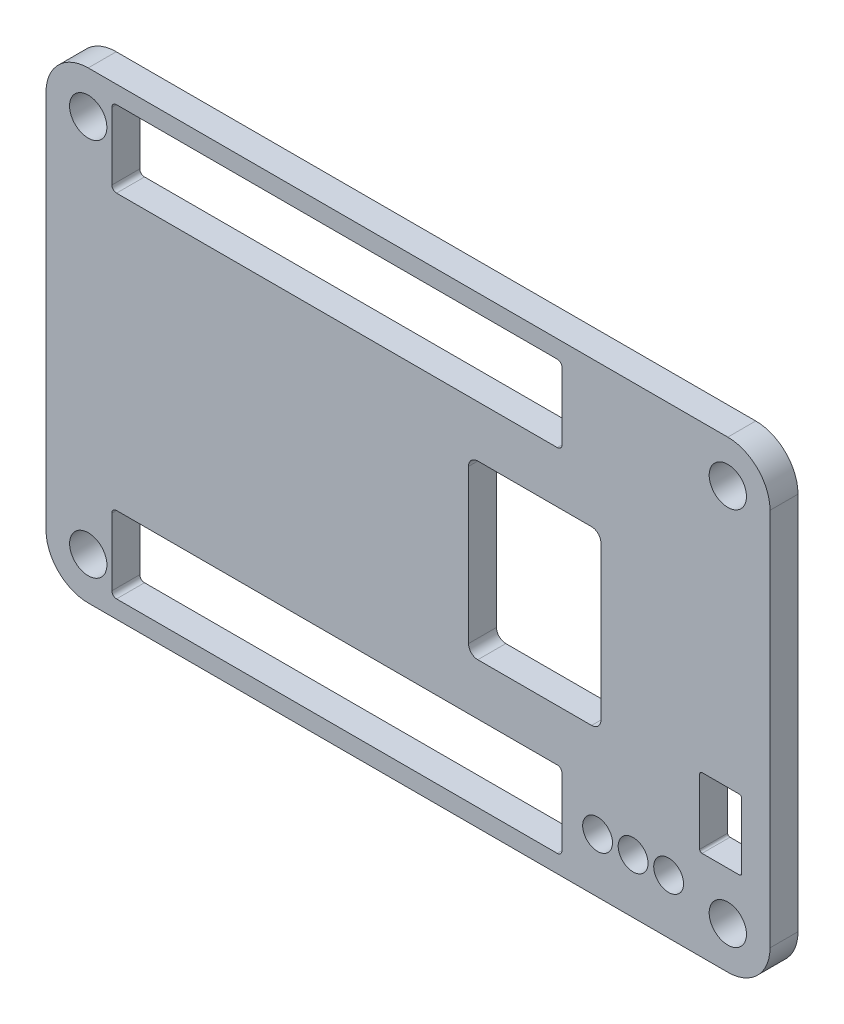
SolidWorks part; units mm, degrees
ref_plane "前视基准面" through (0, 0, 0) normal (0, 0, 1) x (1, 0, 0)
ref_plane "上视基准面" through (0, 0, 0) normal (0, 1, 0) x (1, 0, 0)
ref_plane "右视基准面" through (0, 0, 0) normal (1, 0, 0) x (0, 0, -1)
sketch "草图1" plane through (0, 0, 0) normal (0, 0, 1) x (1, 0, 0)
  line L0 (-34.285, 24.845) -> (34.285, 24.845)
  line L1 (-34.285, 22.845) -> (34.285, 22.845) construction
  line L2 (-36.815, 20.315) -> (-36.815, -20.315) construction
  line L3 (-34.285, -22.845) -> (34.285, -22.845) construction
  line L4 (36.815, 20.315) -> (36.815, -20.315) construction
  line L5 (-36.815, 22.845) -> (36.815, -22.845) construction
  line L6 (-36.815, -22.845) -> (36.815, 22.845) construction
  line L7 (-34.29, 20.32) -> (34.29, 20.32) construction
  line L8 (-34.29, 20.32) -> (-34.29, -20.32) construction
  line L9 (-34.29, -20.32) -> (34.29, -20.32) construction
  line L10 (34.29, 20.32) -> (34.29, -20.32) construction
  line L11 (-34.29, 20.32) -> (34.29, -20.32) construction
  line L12 (-34.29, -20.32) -> (34.29, 20.32) construction
  line L13 (38.815, 20.315) -> (38.815, -20.315)
  line L14 (-34.285, -24.845) -> (34.285, -24.845)
  line L15 (-38.815, 20.315) -> (-38.815, -20.315)
  arc A0 (-36.815, -20.315) -> (-34.285, -22.845) centre (-34.285, -20.315) ccw construction
  arc A1 (34.285, -22.845) -> (36.815, -20.315) centre (34.285, -20.315) ccw construction
  arc A2 (36.815, 20.315) -> (34.285, 22.845) centre (34.285, 20.315) ccw construction
  arc A3 (-36.815, 20.315) -> (-34.285, 22.845) centre (-34.285, 20.315) cw construction
  circle A4 centre (34.29, 20.32) radius 2
  circle A5 centre (34.29, -20.32) radius 2
  circle A6 centre (-34.29, 20.32) radius 2
  circle A7 centre (-34.285, -20.315) radius 2
  arc A8 (38.815, 20.315) -> (34.285, 24.845) centre (34.285, 20.315) ccw
  arc A9 (34.285, -24.845) -> (38.815, -20.315) centre (34.285, -20.315) ccw
  arc A10 (-38.815, -20.315) -> (-34.285, -24.845) centre (-34.285, -20.315) ccw
  arc A11 (-38.815, 20.315) -> (-34.285, 24.845) centre (-34.285, 20.315) cw
  point P0 (0, 0)
  point P18 (0, 0)
  dimension "D3" = 2.53
  dimension "D6" = 4
  dimension "D7" = 4
  dimension "D8" = 4
  dimension "D9" = 4
  dimension "D1" = 73.63
  dimension "D2" = 45.69
  dimension "D4" = 68.58
  dimension "D5" = 40.64
  dimension "D10" = 2
extrude "凸台-拉伸1" add sketch "草图1" along normal mid plane 3
sketch "草图2" plane through (0, 0, 1.5) normal (0, 0, 1) x (1, 0, 0)
  line L0 (-38.815, 20.315) -> (-38.815, -20.315) construction
  line L1 (-31.255, 22.945) -> (16.005, 22.945)
  line L2 (-31.755, 22.445) -> (-31.755, 15.235)
  line L3 (-31.255, 14.735) -> (16.005, 14.735)
  line L4 (16.505, 22.445) -> (16.505, 15.235)
  line L5 (-31.755, 22.945) -> (16.505, 14.735) construction
  line L6 (-31.755, 14.735) -> (16.505, 22.945) construction
  line L7 (38.815, -20.315) -> (38.815, 20.315) construction
  line L8 (34.285, 24.845) -> (-34.285, 24.845) construction
  line L9 (0, 0) -> (13.585, 0) construction
  line L10 (-31.755, -22.445) -> (-31.755, -15.235)
  line L11 (-31.255, -22.945) -> (16.005, -22.945)
  line L12 (16.505, -22.445) -> (16.505, -15.235)
  line L13 (-31.255, -14.735) -> (16.005, -14.735)
  line L14 (-34.285, -24.845) -> (34.285, -24.845) construction
  line L16 (31.525, -7.685) -> (35.525, -7.685)
  line L17 (31.275, -7.935) -> (31.275, -14.935)
  line L18 (31.525, -15.185) -> (35.525, -15.185)
  line L19 (35.775, -7.935) -> (35.775, -14.935)
  line L20 (31.275, -7.685) -> (35.775, -15.185) construction
  line L21 (31.275, -15.185) -> (35.775, -7.685) construction
  line L22 (7.485, 9.225) -> (19.685, 9.225)
  line L23 (6.485, 8.225) -> (6.485, -8.225)
  line L24 (7.485, -9.225) -> (19.685, -9.225)
  line L25 (20.685, 8.225) -> (20.685, -8.225)
  line L26 (6.485, 9.225) -> (20.685, -9.225) construction
  line L27 (6.485, -9.225) -> (20.685, 9.225) construction
  arc A0 (-31.255, 14.735) -> (-31.755, 15.235) centre (-31.255, 15.235) cw
  arc A1 (-31.755, 22.445) -> (-31.255, 22.945) centre (-31.255, 22.445) cw
  arc A2 (16.005, 22.945) -> (16.505, 22.445) centre (16.005, 22.445) cw
  arc A3 (16.505, 15.235) -> (16.005, 14.735) centre (16.005, 15.235) cw
  arc A4 (-31.255, -14.735) -> (-31.755, -15.235) centre (-31.255, -15.235) ccw
  arc A5 (-31.755, -22.445) -> (-31.255, -22.945) centre (-31.255, -22.445) ccw
  arc A6 (16.005, -22.945) -> (16.505, -22.445) centre (16.005, -22.445) ccw
  arc A7 (16.505, -15.235) -> (16.005, -14.735) centre (16.005, -15.235) ccw
  circle A8 centre (27.945, -19.005) radius 1.6
  circle A9 centre (24.135, -19.005) radius 1.6
  circle A10 centre (20.325, -19.005) radius 1.6
  arc A11 (31.275, -14.935) -> (31.525, -15.185) centre (31.525, -14.935) ccw
  arc A12 (35.525, -15.185) -> (35.775, -14.935) centre (35.525, -14.935) ccw
  arc A13 (31.275, -7.935) -> (31.525, -7.685) centre (31.525, -7.935) cw
  arc A14 (35.525, -7.685) -> (35.775, -7.935) centre (35.525, -7.935) cw
  arc A15 (6.485, -8.225) -> (7.485, -9.225) centre (7.485, -8.225) ccw
  arc A16 (19.685, -9.225) -> (20.685, -8.225) centre (19.685, -8.225) ccw
  arc A17 (20.685, 8.225) -> (19.685, 9.225) centre (19.685, 8.225) ccw
  arc A18 (6.485, 8.225) -> (7.485, 9.225) centre (7.485, 8.225) cw
  point P0 (-7.625, 18.84)
  point P42 (33.525, -11.435)
  dimension "D5" = 0.5
  dimension "D6" = 3.2
  dimension "D14" = 0.25
  dimension "D18" = 1
  dimension "D1" = 7.06
  dimension "D2" = 22.31
  dimension "D3" = 10.11
  dimension "D4" = 1.9
  dimension "D7" = 5.84
  dimension "D8" = 10.87
  dimension "D10" = 5.29
  dimension "D11" = 13.41
  dimension "D12" = 7.5
  dimension "D13" = 4.5
  dimension "D15" = 15.62
  dimension "D16" = 18.13
  dimension "D17" = 25.23
  dimension "D9" = 3
extrude "切除-拉伸1" cut sketch "草图2" against normal blind 3
